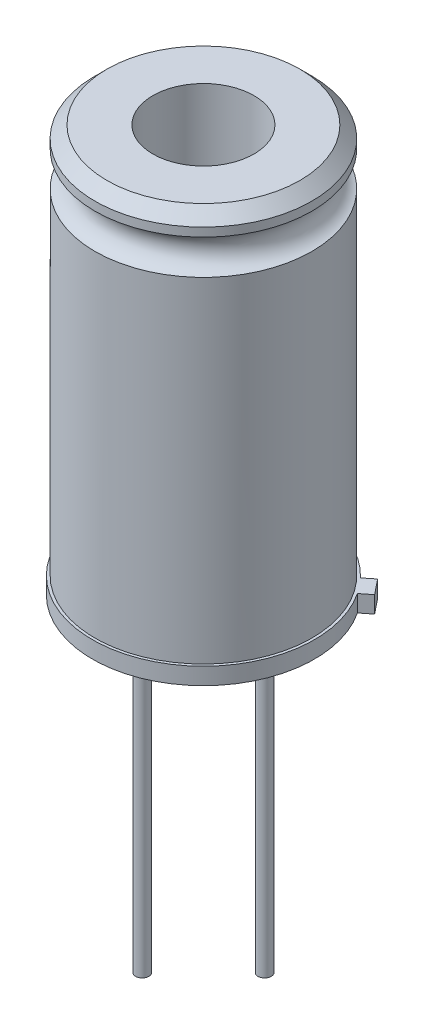
SolidWorks part; units mm, degrees
ref_plane "Plano frontal" through (0, 0, 0) normal (0, 0, 1) x (1, 0, 0)
ref_plane "Plano superior" through (0, 0, 0) normal (0, 1, 0) x (1, 0, 0)
ref_plane "Plano direito" through (0, 0, 0) normal (1, 0, 0) x (0, 0, -1)
sketch "Esboço2" plane through (0, 0, 0) normal (0, 1, 0) x (1, 0, 0)
  line L0 (-4.5, 0) -> (4.5, 0) construction
  line L1 (0, -4.5) -> (0, 4.5) construction
  circle A0 centre (0, 0) radius 4.5
  circle A1 centre (0, 0) radius 2.54 construction
  circle A2 centre (2.54, 0) radius 0.275 construction
  circle A3 centre (0, -2.54) radius 0.275 construction
  circle A4 centre (-2.54, 0) radius 0.275 construction
  circle A5 centre (0, 2.54) radius 0.275 construction
  point P8 (2.54, 0)
  point P20 (0, 0)
  dimension "D1" = 4
extrude "Ressalto-extrusão1" add sketch "Esboço2" along normal blind 16.2
sketch "Esboço3" plane through (0, 16.2, 0) normal (0, 1, 0) x (1, 0, 0)
  circle A0 centre (0, 0) radius 2.1
  point P0 (0, 0)
extrude "Corte-extrusão2" cut sketch "Esboço3" against normal blind 13.2 contours A0
sketch "Esboço5" plane through (0, 0, 0) normal (1, 0, 0) x (0, 0, -1)
  line L0 (4.5, 16.2) -> (-4.5, 16.2) construction
  circle A0 centre (4.7, 14.62) radius 0.75
  dimension "D1" = 1.58
  dimension "D2" = 4.7
revolve "Corte-Revolução1" cut sketch "Esboço5" angle 360 about axis through (0, 16.2, 0) along (0, -1, 0)
sketch "Esboço6" plane through (0, 0, 0) normal (0, 1, 0) x (1, 0, 0)
  circle A0 centre (0, 0) radius 2.54 construction
sketch "Esboço8" plane through (0, 0, 0) normal (0, -1, 0) x (-1, 0, 0)
  line L0 (0, -4.5) -> (0, 4.5) construction
  line L1 (4.5, 0) -> (-4.5, 0) construction
  circle A0 centre (0, 0) radius 4.5 construction
  circle A1 centre (0, 0) radius 2.54 construction
  circle A2 centre (-2.54, 0) radius 0.275
  circle A3 centre (0, 2.54) radius 0.275
  circle A4 centre (2.54, 0) radius 0.275
  circle A5 centre (0, -2.54) radius 0.275
  point P10 (-2.54, 0)
  point P22 (0, 0)
  dimension "D1" = 4
sketch "Esboço11" plane through (0, 0, 0) normal (0, 1, 0) x (1, 0, 0)
  line L0 (-4.5, 0) -> (4.5, 0) construction
  circle A0 centre (2.54, 0) radius 0.8
  circle A1 centre (0, 0) radius 2.54 construction
  circle A2 centre (0, -2.54) radius 0.8
  circle A3 centre (-2.54, 0) radius 0.8
  circle A4 centre (0, 2.54) radius 0.8
  point P15 (0, 0)
  dimension "D1" = 4
sketch "Esboço12" plane through (0, 0, 0) normal (0, -1, 0) x (1, 0, 0)
  line L0 (0, 0) -> (3.9885, -3.1783) construction
  line L1 (3.3421, -3.1747) -> (3.7392, -3.4912)
  line L3 (3.7392, -3.4912) -> (4.2378, -2.8655)
  line L4 (3.8407, -2.5491) -> (4.2378, -2.8655)
  arc A0 (3.8407, -2.5491) -> (3.3421, -3.1747) centre (0, 0) ccw
  dimension "D1" = 0.8
extrude "Ressalto-extrusão2" add sketch "Esboço12" along normal blind 0.7
extrude "Corte-extrusão3" cut sketch "Esboço11" against normal blind 0.7
sketch "Esboço13" plane through (0, -0.7, 0) normal (0, -1, 0) x (-1, 0, 0)
sketch "Esboço14" plane through (0, 0, 0) normal (0, -1, 0) x (-1, 0, 0)
extrude "Ressalto-extrusão3" add sketch "Esboço8" along normal blind 13
sketch "Esboço15" plane through (0, 0, 0) normal (1, 0, 0) x (0, 0, -1)
  line L0 (4.5, 16.2038) -> (4.5, 15.7038)
  line L1 (4.5, 15.3428) -> (4.5, 16.2) construction
  line L2 (4, 16.2048) -> (4.5, 15.7038)
  line L3 (4, 16.2048) -> (4.5, 16.2038)
  dimension "D1" = 0.5
  dimension "D2" = 0.5
revolve "Corte-Revolução2" cut sketch "Esboço15" angle 360
